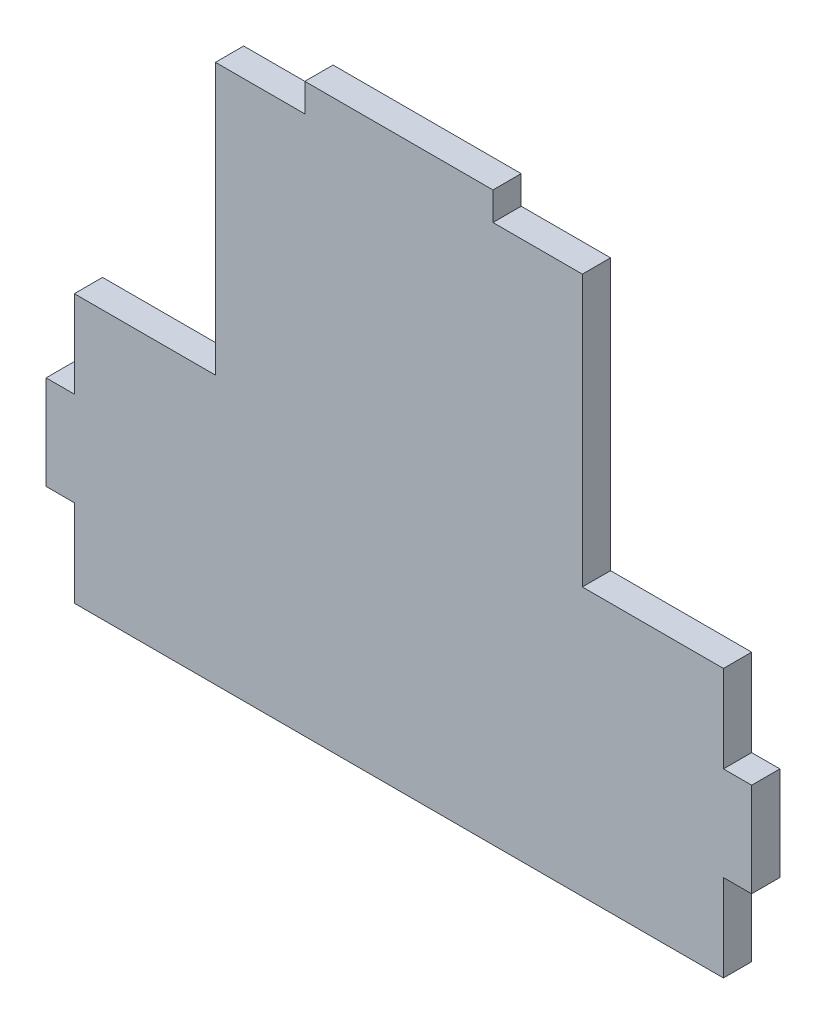
SolidWorks part; units mm, degrees
ref_plane "Alzado" through (0, 0, 0) normal (0, 0, 1) x (1, 0, 0)
ref_plane "Planta" through (0, 0, 0) normal (0, 1, 0) x (1, 0, 0)
ref_plane "Vista lateral" through (0, 0, 0) normal (1, 0, 0) x (0, 0, -1)
sketch "Croquis1" plane through (0, 0, 0) normal (0, 0, 1) x (1, 0, 0)
  line L0 (18, -3) -> (57, -3)
  line L1 (18, -3) -> (18, -31.8)
  line L2 (18, -31.8) -> (3, -31.8)
  line L4 (3, -31.8) -> (3, -60.3)
  line L5 (3, -60.3) -> (72, -60.3)
  line L6 (72, -60.3) -> (72, -31.8)
  line L7 (72, -31.8) -> (57, -31.8)
  line L8 (57, -31.8) -> (57, -3)
  point P4 (0, 0)
  dimension "D1" = 28.5
extrude "Saliente-Extruir1" add sketch "Croquis1" along normal blind 3
sketch "Croquis2" plane through (0, 0, 3) normal (0, 0, 1) x (1, 0, 0)
  line L0 (72, -41.05) -> (75, -41.05)
  line L1 (72, -60.3) -> (72, -31.8) construction
  line L2 (75, -41.05) -> (75, -51.05)
  line L3 (75, -51.05) -> (72, -51.05)
  line L4 (72, -51.05) -> (72, -41.05)
  line L5 (3, -31.8) -> (3, -60.3) construction
  line L7 (3, -41.05) -> (0, -41.05)
  line L8 (3, -41.05) -> (3, -51.05)
  line L9 (3, -51.05) -> (0, -51.05)
  line L10 (0, -41.05) -> (0, -51.05)
  line L11 (57, -3) -> (18, -3) construction
  line L12 (27.5, -3) -> (47.5, -3)
  line L13 (27.5, -3) -> (27.5, 0)
  line L14 (27.5, 0) -> (47.5, 0)
  line L15 (47.5, -3) -> (47.5, 0)
  dimension "D1" = 10
  dimension "D2" = 9.25
  dimension "D3" = 3
  dimension "D4" = 10
  dimension "D5" = 3
  dimension "D6" = 9.25
  dimension "D7" = 20
  dimension "D8" = 9.5
  dimension "D9" = 3
extrude "Saliente-Extruir2" add sketch "Croquis2" against normal blind 3
